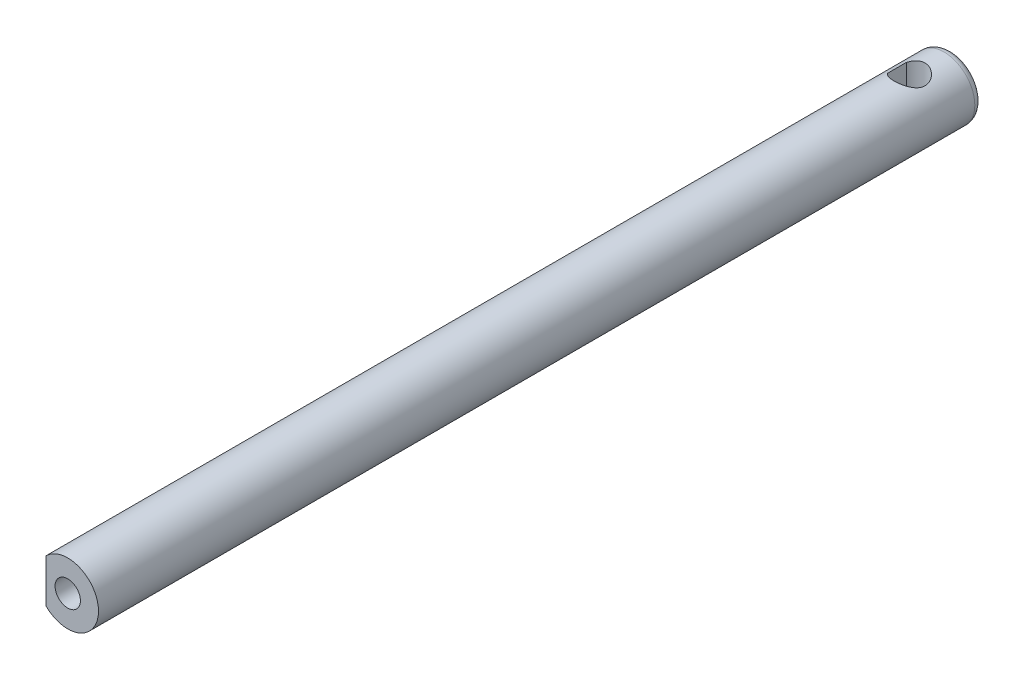
SolidWorks part; units mm, degrees
ref_plane "前视基准面" through (0, 0, 0) normal (0, 0, 1) x (1, 0, 0)
ref_plane "上视基准面" through (0, 0, 0) normal (0, 1, 0) x (1, 0, 0)
ref_plane "右视基准面" through (0, 0, 0) normal (1, 0, 0) x (0, 0, -1)
sketch "草图1" plane through (0, 0, 0) normal (0, 1, 0) x (1, 0, 0)
  line L0 (2.025, 52) -> (-1.625, 52) construction
  line L1 (-4, -55) -> (4, -55) construction
  line L2 (-4, -55) -> (-4, 55) construction
  line L3 (-4, 55) -> (4, 55) construction
  line L4 (4, -55) -> (4, 55) construction
  line L5 (0, 55) -> (0, -55) construction
  line L6 (-4, 0) -> (4, 0) construction
  line L7 (-1.625, 50.7917) -> (-1.625, 53.2083)
  arc A1 (-1.625, 50.7917) -> (-1.625, 53.2083) centre (0, 52) ccw
  point P0 (0, 0)
  dimension "D1" = 110
  dimension "D4" = 4.05
  dimension "D2" = 8
  dimension "D3" = 3
  dimension "D5" = 3.65
sketch "草图3" plane through (0, 0, 0) normal (0, 0, 1) x (1, 0, 0)
  circle A0 centre (0, 0) radius 4
  dimension "D1" = 8
extrude "凸台-拉伸2" add sketch "草图3" along normal mid plane 115
extrude "切除-拉伸1" cut sketch "草图1" against normal through all both and the other way through all
sketch "草图4" plane through (-1.625, 0, 0) normal (1, 0, 0) x (0, 0, -1)
  line L0 (53.2083, 3.655) -> (50.7917, -3.655) construction
  line L1 (53.2083, -3.655) -> (50.7917, 3.655) construction
  line L4 (50.7917, 3.655) -> (50.7917, -3.655)
  line L5 (50.7917, -3.655) -> (53.2083, -3.655)
  line L6 (53.2083, -3.655) -> (53.2083, 3.655)
  line L7 (53.2083, 3.655) -> (50.7917, 3.655)
  line L8 (50.7917, 3.655) -> (50.7917, -3.655) construction
  line L9 (50.7917, -3.655) -> (53.2083, -3.655) construction
  line L10 (53.2083, -3.655) -> (53.2083, 3.655) construction
  line L11 (53.2083, 3.655) -> (50.7917, 3.655) construction
  circle A0 centre (52, 0) radius 1.35
  point P2 (52, 0)
  dimension "D2" = 2.7
  dimension "D1" = 0
sketch "草图13" plane through (0, 0, 57.5) normal (0, 0, 1) x (1, 0, 0)
  line L0 (-2.8284, -2.8284) -> (-2.8284, 2.8284)
  line L1 (-2.8284, 2.8284) -> (2.8284, 2.8284)
  line L2 (2.8284, 2.8284) -> (2.8284, -2.8284)
  line L3 (2.8284, -2.8284) -> (-2.8284, -2.8284)
  line L4 (0, 0) -> (1.5958, 0) construction
  circle A1 centre (0, 0) radius 4
  circle A2 centre (0, 0) radius 4
  circle M7 centre (0, 0) radius 4
  dimension "D1" = 0
fillet "圆角1" radius 1 1 edges at (4, 0, -57.5)
hole_wizard "M4x0.7 螺纹孔1" positions "草图14" profile "草图15" tap size "M4x0.7" standard "ANSI Metric"
sketch "草图14" plane through (0, 0, 57.5) normal (0, 0, 1) x (1, 0, 0)
  point P0 (0, 0)
cosmetic thread "孔螺蚊线1" parameters "D1"=10, "D2"=4
sketch "草图15" plane through (0, 0, 57.5) normal (1, 0, 0) x (0, -1, 0)
  line L0 (0, 0) -> (0, 10.9914)
  line L1 (0, 10.9914) -> (1.65, 10)
  line L2 (1.65, 10) -> (1.65, 0)
  line L5 (1.65, 0) -> (0, 0)
  line L10 (0, 10.9914) -> (-1.65, 10) construction
  line L11 (0, -6.35) -> (0, 107.95) construction
  dimension "螺纹孔钻头直径" = 3.3
  dimension "螺纹孔钻头深度" = 10
  dimension "导头角度" = 118
hole_wizard "M3x0.5 螺纹孔1" positions "草图16" profile "草图17" tap size "M3x0.5" standard "ANSI Metric"
sketch "草图16" plane through (-1.625, 0, 0) normal (1, 0, 0) x (0, 0, -1)
  point P0 (52, 0)
sketch "草图17" plane through (-1.625, 0, -52) normal (0, 1, 0) x (0, 0, -1)
  line L0 (0, 0) -> (0, 8.2511)
  line L1 (0, 8.2511) -> (1.25, 7.5)
  line L2 (1.25, 7.5) -> (1.25, 0)
  line L5 (1.25, 0) -> (0, 0)
  line L10 (0, 8.2511) -> (-1.25, 7.5) construction
  line L11 (0, -6.35) -> (0, 107.95) construction
  dimension "螺纹孔钻头直径" = 2.5
  dimension "螺纹孔钻头深度" = 7.5
  dimension "导头角度" = 118
extrude "切除-拉伸2" cut sketch "草图13" against normal blind 30 contours L4 L0 M7 | L4 A2 L0
